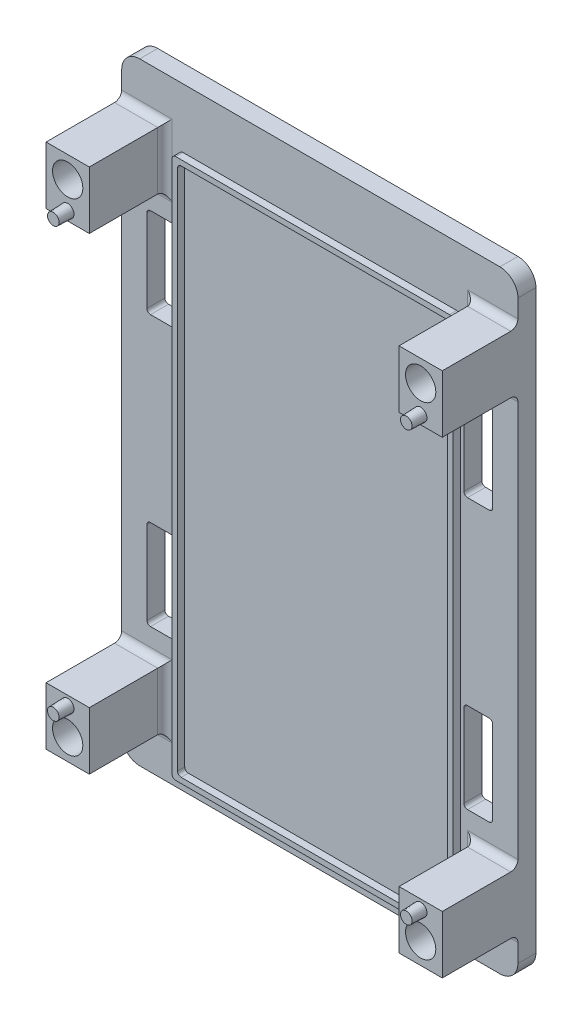
SolidWorks part; units mm, degrees
ref_plane "Ebene vorne" through (0, 0, 0) normal (0, 0, 1) x (1, 0, 0)
ref_plane "Ebene oben" through (0, 0, 0) normal (0, 1, 0) x (1, 0, 0)
ref_plane "Ebene rechts" through (0, 0, 0) normal (1, 0, 0) x (0, 0, -1)
sketch "Skizze1" plane through (0, 0, 0) normal (0, 0, 1) x (1, 0, 0)
  line L1 (-55, -85) -> (55, -85)
  line L2 (-55, -85) -> (-55, 85)
  line L3 (-55, 85) -> (55, 85)
  line L4 (55, -85) -> (55, 85)
  line L5 (-55, -85) -> (55, 85) construction
  line L6 (-55, 85) -> (55, -85) construction
  point P0 (0, 0)
  dimension "D1" = 110
  dimension "D2" = 170
extrude "Aufsatz-Linear austragen1" add sketch "Skizze1" along normal blind 5
fillet "Verrundung1" radius 5 4 edges at (-55, -85, 2.5) (55, -85, 2.5) (55, 85, 2.5) (-55, 85, 2.5)
sketch "Skizze7" plane through (0, 0, 5) normal (0, 0, 1) x (1, 0, 0)
  line L0 (-55, 80) -> (-55, -80) construction
  line L1 (-55, 73) -> (-43, 73)
  line L2 (-55, 73) -> (-55, 57)
  line L3 (-55, 57) -> (-43, 57)
  line L4 (-43, 73) -> (-43, 57)
  line L5 (50, 85) -> (-50, 85) construction
  line L18 (0, 85) -> (0, -85) construction
  line L19 (-50, -85) -> (50, -85) construction
  line L20 (-55, 0) -> (55, 0) construction
  line L21 (55, -80) -> (55, 80) construction
  line L22 (43, 73) -> (43, 57)
  line L23 (55, 57) -> (43, 57)
  line L24 (55, 73) -> (55, 57)
  line L25 (55, 73) -> (43, 73)
  line L26 (55, -73) -> (43, -73)
  line L27 (55, -73) -> (55, -57)
  line L28 (55, -57) -> (43, -57)
  line L29 (43, -73) -> (43, -57)
  line L30 (-43, -73) -> (-43, -57)
  line L31 (-55, -57) -> (-43, -57)
  line L32 (-55, -73) -> (-55, -57)
  line L33 (-55, -73) -> (-43, -73)
  dimension "D1" = 12
  dimension "D2" = 16
  dimension "D3" = 12
extrude "Aufsatz-Linear austragen3" add sketch "Skizze7" along normal blind 21
fillet "Verrundung2" radius 2 12 edges at (-49, 73, 5) (-49, 57, 5) (-43, 65, 5) (-49, -57, 5) (-43, -65, 5) (-49, -73, 5) (49, -73, 5) (43, -65, 5) (49, -57, 5) (49, 57, 5) (43, 65, 5) (49, 73, 5)
sketch "Skizze8" plane through (0, 0, 26) normal (0, 0, 1) x (1, 0, 0)
  line L0 (-43, 73) -> (-55, 73) construction
  line L1 (-55, 80) -> (-55, 75) construction
  line L5 (-55, 31.954) -> (-55, -16.1316) construction
  line L8 (-55, 55) -> (-55, -55) construction
  circle A1 centre (-49, 67) radius 4.2
  dimension "D1" = 8.4
  dimension "D2" = 6
  dimension "D3" = 6
extrude "Schnitt-Linear austragen3" cut sketch "Skizze8" against normal through all
pattern_linear "Lineares Muster1" count 2 spacing 134 along (0, -1, 0) count 2 spacing 98 along (1, 0, 0) of "Schnitt-Linear austragen3"
sketch "Skizze11" plane through (0, 0, 5) normal (0, 0, 1) x (1, 0, 0)
  line L0 (0, 85) -> (0, -85) construction
  line L1 (-37.5, -80) -> (37.5, -80)
  line L2 (-37.5, -80) -> (-37.5, 67)
  line L3 (-37.5, 67) -> (37.5, 67)
  line L4 (37.5, -80) -> (37.5, 67)
  line L5 (-37.5, -80) -> (37.5, 67) construction
  line L6 (-37.5, 67) -> (37.5, -80) construction
  line L7 (50, 85) -> (-50, 85) construction
  line L8 (-50, -85) -> (50, -85) construction
  line L10 (-39, -81.5) -> (39, -81.5)
  line L11 (-39, -81.5) -> (-39, 68.5)
  line L12 (-39, 68.5) -> (39, 68.5)
  line L13 (39, -81.5) -> (39, 68.5)
  line L14 (-39, -81.5) -> (39, 68.5) construction
  line L15 (-39, 68.5) -> (39, -81.5) construction
  point P0 (0, 0)
  point P6 (0, -6.5)
  dimension "D1" = 75
  dimension "D2" = 37.5
  dimension "D3" = 5
  dimension "D4" = 147
  dimension "D5" = 150
  dimension "D6" = 78
extrude "Aufsatz-Linear austragen4" add sketch "Skizze11" along normal blind 2
fillet "Verrundung3" radius 1 8 edges at (37.5, -80, 6) (39, -81.5, 6) (-37.5, -80, 6) (-39, -81.5, 6) (37.5, 67, 6) (39, 68.5, 6) (-39, 68.5, 6) (-37.5, 67, 6)
sketch "Skizze12" plane through (0, 0, 5) normal (0, 0, 1) x (1, 0, 0)
  line L0 (-55, 55) -> (-55, -55) construction
  line L1 (-48, 25) -> (-40, 25)
  line L2 (-48, 25) -> (-48, 50)
  line L3 (-48, 50) -> (-40, 50)
  line L4 (-40, 25) -> (-40, 50)
  line L5 (-48, 25) -> (-40, 50) construction
  line L6 (-48, 50) -> (-40, 25) construction
  line L7 (50, 85) -> (-50, 85) construction
  line L8 (0, 85) -> (0, -85) construction
  line L9 (-50, -85) -> (50, -85) construction
  line L10 (-55, 0) -> (55, 0) construction
  line L11 (55, -55) -> (55, 55) construction
  line L12 (48, 50) -> (40, 50)
  line L13 (40, 25) -> (40, 50)
  line L14 (48, 25) -> (40, 25)
  line L15 (48, 25) -> (48, 50)
  line L16 (48, -25) -> (48, -50)
  line L17 (48, -25) -> (40, -25)
  line L18 (40, -25) -> (40, -50)
  line L19 (48, -50) -> (40, -50)
  line L20 (-48, -50) -> (-40, -50)
  line L21 (-40, -25) -> (-40, -50)
  line L22 (-48, -25) -> (-40, -25)
  line L23 (-48, -25) -> (-48, -50)
  point P0 (-44, 37.5)
  dimension "D1" = 8
  dimension "D2" = 7
  dimension "D3" = 25
  dimension "D4" = 35
extrude "Schnitt-Linear austragen4" cut sketch "Skizze12" against normal through all
sketch "Skizze13" plane through (0, 0, 26) normal (0, 0, 1) x (1, 0, 0)
  line L0 (-49, 73) -> (-49, 57) construction
  line L1 (-43, 73) -> (-55, 73) construction
  line L2 (-55, 57) -> (-43, 57) construction
  line L3 (-43, 67) -> (-55, 67) construction
  line L4 (-43, 57) -> (-43, 73) construction
  line L5 (-55, 73) -> (-55, 57) construction
  line L6 (0, 85) -> (0, -85) construction
  line L7 (50, 85) -> (-50, 85) construction
  line L8 (-50, -85) -> (50, -85) construction
  line L9 (-55, 0) -> (55, 0) construction
  line L10 (-55, 55) -> (-55, -55) construction
  line L11 (55, -55) -> (55, 55) construction
  circle A1 centre (-49, 59.5) radius 1.75
  circle A2 centre (49, 59.5) radius 1.75
  circle A3 centre (49, -59.5) radius 1.75
  circle A4 centre (-49, -59.5) radius 1.75
  dimension "D1" = 3.5
  dimension "D2" = 7.5
extrude "Aufsatz-Linear austragen5" add sketch "Skizze13" along normal blind 4 draft 2
sketch "Skizze14" plane through (0, 0, 0) normal (0, 0, -1) x (-1, 0, 0)
  line L0 (49, 71.2) -> (49, 62.8) construction
  line L1 (44.8, 67) -> (53.2, 67) construction
  line L2 (0, 85) -> (0, -85) construction
  line L3 (-50, 85) -> (50, 85) construction
  line L4 (50, -85) -> (-50, -85) construction
  line L5 (-55, 0) -> (55, 0) construction
  line L6 (-55, -80) -> (-55, 80) construction
  line L7 (55, 80) -> (55, -80) construction
  circle A0 centre (49, 67) radius 4.2 construction
  circle A1 centre (49, 59.5) radius 2
  circle A2 centre (-49, 59.5) radius 2
  circle A3 centre (-49, -59.5) radius 2
  circle A4 centre (49, -59.5) radius 2
  dimension "D1" = 4
  dimension "D2" = 7.5
extrude "Schnitt-Linear austragen5" cut sketch "Skizze14" against normal blind 4.5
fillet "Verrundung4" radius 1 16 edges at (40, -25, 2.5) (48, -25, 2.5) (40, -50, 2.5) (48, -50, 2.5) (-40, -50, 2.5) (-48, -50, 2.5) (-40, -25, 2.5) (-48, -25, 2.5) (40, 50, 2.5) (48, 50, 2.5) (40, 25, 2.5) (48, 25, 2.5) (-40, 25, 2.5) (-48, 25, 2.5) (-40, 50, 2.5) (-48, 50, 2.5)
